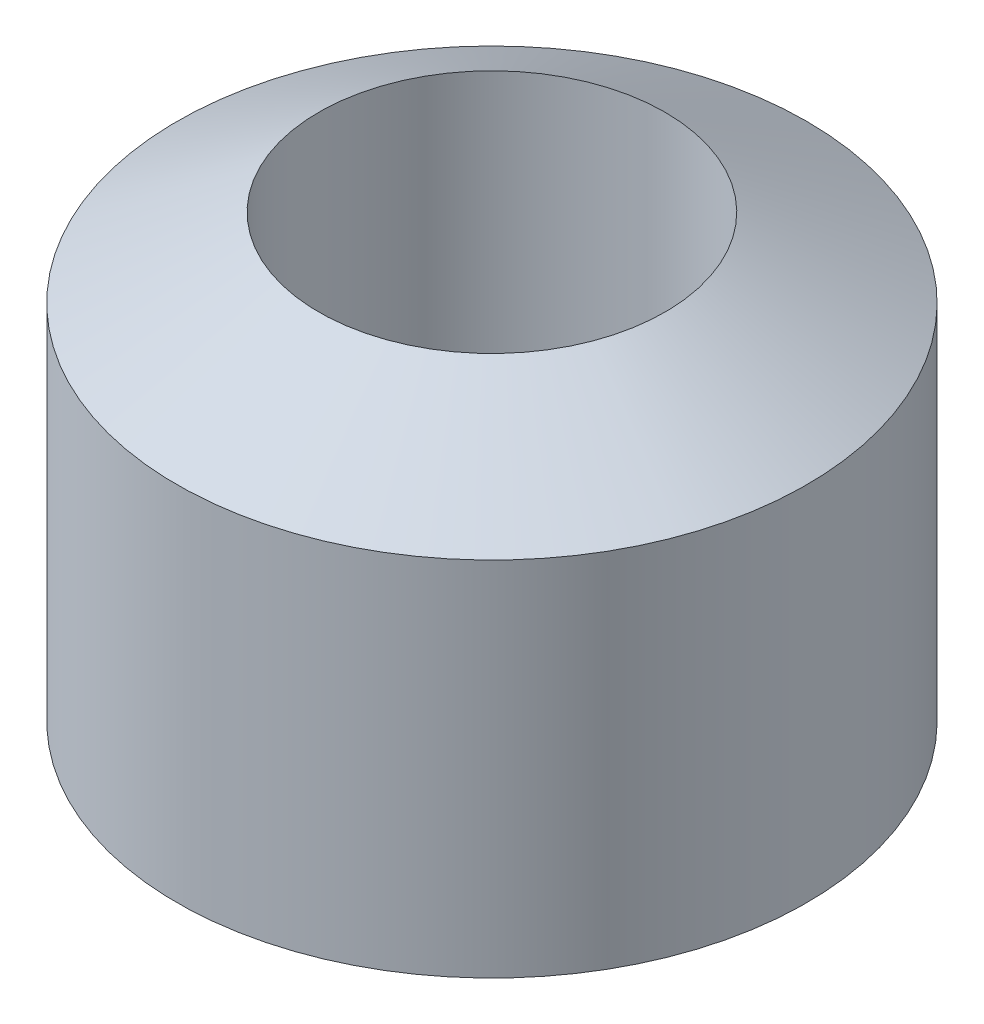
SolidWorks part; units mm, degrees
ref_plane "Front Plane" through (0, 0, 0) normal (0, 0, 1) x (1, 0, 0)
ref_plane "Top Plane" through (0, 0, 0) normal (0, 1, 0) x (1, 0, 0)
ref_plane "Right Plane" through (0, 0, 0) normal (1, 0, 0) x (0, 0, -1)
sketch "Sketch1" plane through (0, 0, 0) normal (0, 0, 1) x (1, 0, 0)
  line L0 (5.5, 0) -> (10, 2.5)
  line L1 (10, 2.5) -> (10, 14)
  line L2 (10, 14) -> (5.5, 16.5)
  line L3 (5.5, 0) -> (5.5, 16.5)
  line L4 (0, 0) -> (0, 20.5899) construction
  dimension "D1" = 5.5
  dimension "D2" = 4.5
  dimension "D3" = 2.5
  dimension "D4" = 11.5
  dimension "D5" = 4.5
  dimension "D6" = 2.5
revolve "Revolve1" add sketch "Sketch1" angle 360 about L4
